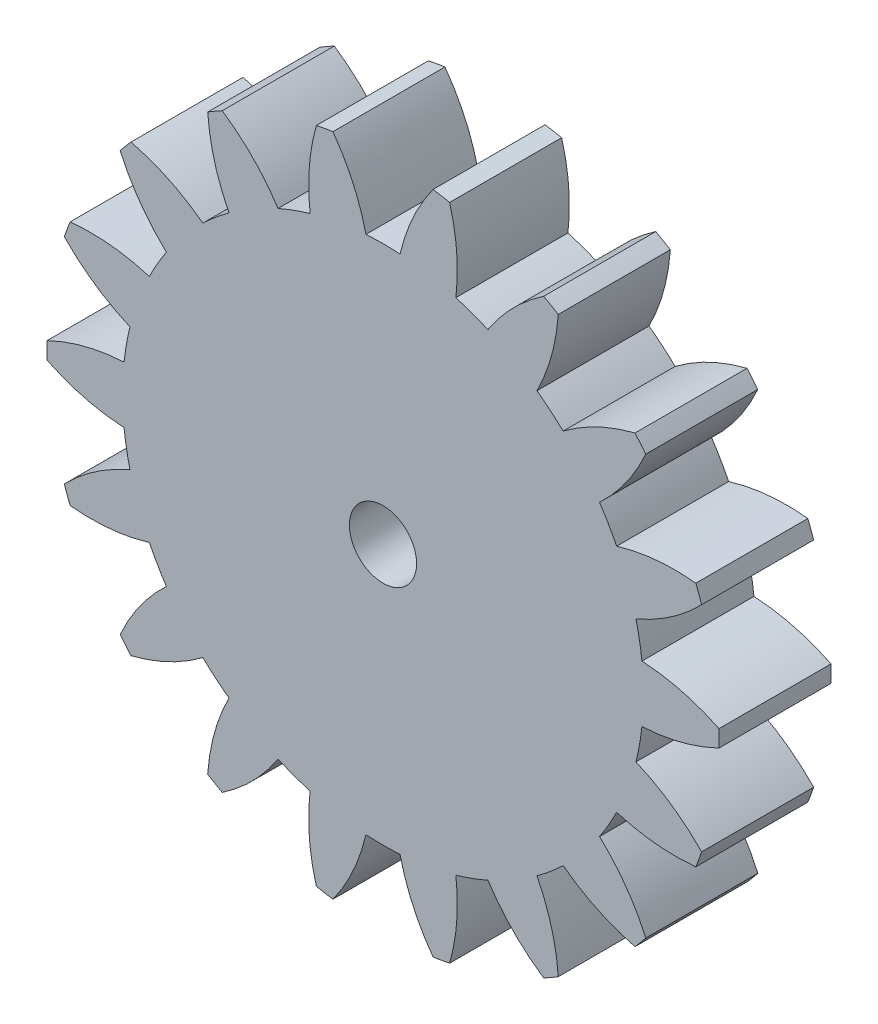
SolidWorks part; units mm, degrees
ref_plane "Front Plane" through (0, 0, 0) normal (0, 0, 1) x (1, 0, 0)
ref_plane "Top Plane" through (0, 0, 0) normal (0, 1, 0) x (1, 0, 0)
ref_plane "Right Plane" through (0, 0, 0) normal (1, 0, 0) x (0, 0, -1)
sketch "Sketch1" plane through (0, 0, 0) normal (0, 0, 1) x (1, 0, 0)
  line L0 (-5.2094, 29.5442) -> (-5.0244, 28.4945) construction
  circle A0 centre (0, 0) radius 3
  arc A1 (-6.5048, 22.3205) -> (-9.3644, 21.2797) centre (0, 0) ccw
  arc A2 (-4.4673, 29.6655) -> (-5.9483, 29.4044) centre (0, 0) ccw
  arc A3 (5.9483, 29.4044) -> (4.4673, 29.6655) centre (0, 0) ccw
  arc A4 (15.6465, 25.5966) -> (14.3441, 26.3486) centre (0, 0) ccw
  arc A5 (23.4575, 18.7015) -> (22.4908, 19.8536) centre (0, 0) ccw
  arc A6 (28.4391, 9.5508) -> (27.9247, 10.964) centre (0, 0) ccw
  arc A7 (29.9906, -0.752) -> (29.9906, 0.752) centre (0, 0) ccw
  arc A8 (27.9247, -10.964) -> (28.4391, -9.5508) centre (0, 0) ccw
  arc A9 (22.4908, -19.8536) -> (23.4575, -18.7015) centre (0, 0) ccw
  arc A10 (14.3441, -26.3486) -> (15.6465, -25.5966) centre (0, 0) ccw
  arc A11 (4.4673, -29.6655) -> (5.9483, -29.4044) centre (0, 0) ccw
  arc A12 (-5.9483, -29.4044) -> (-4.4673, -29.6655) centre (0, 0) ccw
  arc A13 (-15.6465, -25.5966) -> (-14.3441, -26.3486) centre (0, 0) ccw
  arc A14 (-23.4575, -18.7015) -> (-22.4908, -19.8536) centre (0, 0) ccw
  arc A15 (-28.4391, -9.5508) -> (-27.9247, -10.964) centre (0, 0) ccw
  arc A16 (-29.9906, 0.752) -> (-29.9906, -0.752) centre (0, 0) ccw
  arc A17 (-27.9247, 10.964) -> (-28.4391, 9.5508) centre (0, 0) ccw
  arc A18 (-22.4908, 19.8536) -> (-23.4575, 18.7015) centre (0, 0) ccw
  arc A19 (-14.3441, 26.3486) -> (-15.6465, 25.5966) centre (0, 0) ccw
  arc A20 (-13.7466, 18.7496) -> (-16.0777, 16.7936) centre (0, 0) ccw
  arc A21 (-19.3303, 12.9173) -> (-20.8518, 10.2819) centre (0, 0) ccw
  arc A22 (-22.5825, 5.5269) -> (-23.1109, 2.5301) centre (0, 0) ccw
  arc A23 (-23.1109, -2.5301) -> (-22.5825, -5.5269) centre (0, 0) ccw
  arc A24 (-20.8518, -10.2819) -> (-19.3303, -12.9173) centre (0, 0) ccw
  arc A25 (-16.0777, -16.7936) -> (-13.7466, -18.7496) centre (0, 0) ccw
  arc A26 (-9.3644, -21.2797) -> (-6.5048, -22.3205) centre (0, 0) ccw
  arc A27 (-1.5216, -23.1992) -> (1.5216, -23.1992) centre (0, 0) ccw
  arc A28 (6.5048, -22.3205) -> (9.3644, -21.2797) centre (0, 0) ccw
  arc A29 (13.7466, -18.7496) -> (16.0777, -16.7936) centre (0, 0) ccw
  arc A30 (19.3303, -12.9173) -> (20.8518, -10.2819) centre (0, 0) ccw
  arc A31 (22.5825, -5.5269) -> (23.1109, -2.5301) centre (0, 0) ccw
  arc A32 (23.1109, 2.5301) -> (22.5825, 5.5269) centre (0, 0) ccw
  arc A33 (20.8518, 10.2819) -> (19.3303, 12.9173) centre (0, 0) ccw
  arc A34 (16.0777, 16.7936) -> (13.7466, 18.7496) centre (0, 0) ccw
  arc A35 (9.3644, 21.2797) -> (6.5048, 22.3205) centre (0, 0) ccw
  arc A36 (1.5216, 23.1992) -> (-1.5216, 23.1992) centre (0, 0) ccw
  spline S0 degree 2 poles (-5.9483, 29.4044) (-6.9383, 25.9234) (-6.5048, 22.3205) knots 0 0 0 1 1 1
  spline S1 degree 2 poles (-4.4673, 29.6655) (-2.3465, 26.7331) (-1.5216, 23.1992) knots 0 0 0 1 1 1
  spline S2 degree 2 poles (4.4673, 29.6655) (2.3465, 26.7331) (1.5216, 23.1992) knots 0 0 0 1 1 1
  spline S3 degree 2 poles (5.9483, 29.4044) (6.9383, 25.9234) (6.5048, 22.3205) knots 0 0 0 1 1 1
  spline S4 degree 2 poles (14.3441, 26.3486) (11.3482, 24.3183) (9.3644, 21.2797) knots 0 0 0 1 1 1
  spline S5 degree 2 poles (15.6465, 25.5966) (15.3862, 21.987) (13.7466, 18.7496) knots 0 0 0 1 1 1
  spline S6 degree 2 poles (22.4908, 19.8536) (18.9812, 18.9704) (16.0777, 16.7936) knots 0 0 0 1 1 1
  spline S7 degree 2 poles (23.4575, 18.7015) (21.9783, 15.3986) (19.3303, 12.9173) knots 0 0 0 1 1 1
  spline S8 degree 2 poles (27.9247, 10.964) (24.3247, 11.3344) (20.8518, 10.2819) knots 0 0 0 1 1 1
  spline S9 degree 2 poles (28.4391, 9.5508) (25.9195, 6.953) (22.5825, 5.5269) knots 0 0 0 1 1 1
  spline S10 degree 2 poles (29.9906, 0.752) (26.7344, 2.3313) (23.1109, 2.5301) knots 0 0 0 1 1 1
  spline S11 degree 2 poles (29.9906, -0.752) (26.7344, -2.3313) (23.1109, -2.5301) knots 0 0 0 1 1 1
  spline S12 degree 2 poles (28.4391, -9.5508) (25.9195, -6.953) (22.5825, -5.5269) knots 0 0 0 1 1 1
  spline S13 degree 2 poles (27.9247, -10.964) (24.3247, -11.3344) (20.8518, -10.2819) knots 0 0 0 1 1 1
  spline S14 degree 2 poles (23.4575, -18.7015) (21.9783, -15.3986) (19.3303, -12.9173) knots 0 0 0 1 1 1
  spline S15 degree 2 poles (22.4908, -19.8536) (18.9812, -18.9704) (16.0777, -16.7936) knots 0 0 0 1 1 1
  spline S16 degree 2 poles (15.6465, -25.5966) (15.3862, -21.987) (13.7466, -18.7496) knots 0 0 0 1 1 1
  spline S17 degree 2 poles (14.3441, -26.3486) (11.3482, -24.3183) (9.3644, -21.2797) knots 0 0 0 1 1 1
  spline S18 degree 2 poles (5.9483, -29.4044) (6.9383, -25.9234) (6.5048, -22.3205) knots 0 0 0 1 1 1
  spline S19 degree 2 poles (4.4673, -29.6655) (2.3465, -26.7331) (1.5216, -23.1992) knots 0 0 0 1 1 1
  spline S20 degree 2 poles (-4.4673, -29.6655) (-2.3465, -26.7331) (-1.5216, -23.1992) knots 0 0 0 1 1 1
  spline S21 degree 2 poles (-5.9483, -29.4044) (-6.9383, -25.9234) (-6.5048, -22.3205) knots 0 0 0 1 1 1
  spline S22 degree 2 poles (-14.3441, -26.3486) (-11.3482, -24.3183) (-9.3644, -21.2797) knots 0 0 0 1 1 1
  spline S23 degree 2 poles (-15.6465, -25.5966) (-15.3862, -21.987) (-13.7466, -18.7496) knots 0 0 0 1 1 1
  spline S24 degree 2 poles (-22.4908, -19.8536) (-18.9812, -18.9704) (-16.0777, -16.7936) knots 0 0 0 1 1 1
  spline S25 degree 2 poles (-23.4575, -18.7015) (-21.9783, -15.3986) (-19.3303, -12.9173) knots 0 0 0 1 1 1
  spline S26 degree 2 poles (-27.9247, -10.964) (-24.3247, -11.3344) (-20.8518, -10.2819) knots 0 0 0 1 1 1
  spline S27 degree 2 poles (-28.4391, -9.5508) (-25.9195, -6.953) (-22.5825, -5.5269) knots 0 0 0 1 1 1
  spline S28 degree 2 poles (-29.9906, -0.752) (-26.7344, -2.3313) (-23.1109, -2.5301) knots 0 0 0 1 1 1
  spline S29 degree 2 poles (-29.9906, 0.752) (-26.7344, 2.3313) (-23.1109, 2.5301) knots 0 0 0 1 1 1
  spline S30 degree 2 poles (-28.4391, 9.5508) (-25.9195, 6.953) (-22.5825, 5.5269) knots 0 0 0 1 1 1
  spline S31 degree 2 poles (-27.9247, 10.964) (-24.3247, 11.3344) (-20.8518, 10.2819) knots 0 0 0 1 1 1
  spline S32 degree 2 poles (-23.4575, 18.7015) (-21.9783, 15.3986) (-19.3303, 12.9173) knots 0 0 0 1 1 1
  spline S33 degree 2 poles (-22.4908, 19.8536) (-18.9812, 18.9704) (-16.0777, 16.7936) knots 0 0 0 1 1 1
  spline S34 degree 2 poles (-15.6465, 25.5966) (-15.3862, 21.987) (-13.7466, 18.7496) knots 0 0 0 1 1 1
  spline S35 degree 2 poles (-14.3441, 26.3486) (-11.3482, 24.3183) (-9.3644, 21.2797) knots 0 0 0 1 1 1
  dimension "D1" = 6
extrude "Boss-Extrude1" add sketch "Sketch1" along normal blind 10
